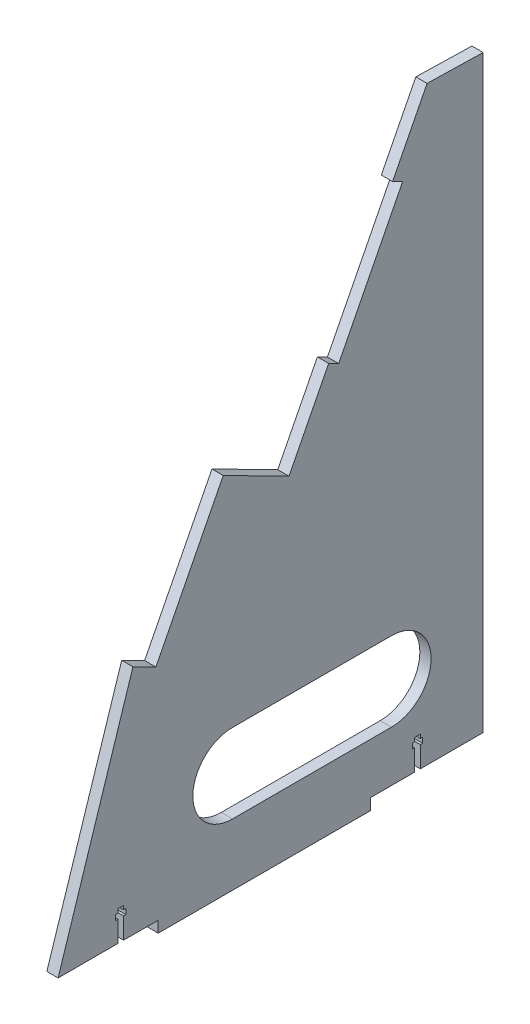
SolidWorks part; units mm, degrees
ref_plane "Front Plane" through (0, 0, 0) normal (0, 0, 1) x (1, 0, 0)
ref_plane "Top Plane" through (0, 0, 0) normal (0, 1, 0) x (1, 0, 0)
ref_plane "Right Plane" through (0, 0, 0) normal (1, 0, 0) x (0, 0, -1)
sketch "Sketch1" plane through (0, 0, 0) normal (1, 0, 0) x (0, 0, -1)
  line L8 (42.308, 123.833) -> (2.4484, 0.2585)
  line L9 (2.4484, 0.2585) -> (228.7682, 0.2585)
  line L10 (228.7682, 0.2585) -> (228.7682, 313.8431)
  line L11 (228.7682, 313.8431) -> (198.91, 314.5312)
  line L12 (125.3885, 170.1754) -> (90.3689, 188.0112)
  line L13 (90.3689, 188.0112) -> (54.5159, 117.6154)
  line L14 (54.5159, 117.6154) -> (42.308, 123.833)
  line L15 (198.91, 314.5312) -> (180.5296, 278.4423)
  line L16 (180.5296, 278.4423) -> (185.8761, 275.7192)
  line L17 (185.8761, 275.7192) -> (151.8384, 208.8879)
  line L18 (151.8384, 208.8879) -> (146.4919, 211.6109)
  line L19 (146.4919, 211.6109) -> (125.3885, 170.1754)
extrude "Boss-Extrude1" add sketch "Sketch1" along normal blind 6
sketch "Sketch2" plane through (6, 0, 0) normal (1, 0, 0) x (0, 0, -1)
  line L0 (95.2866, 48.2606) -> (179.9632, 48.2606) construction
  line L1 (95.2866, 69.3488) -> (179.9632, 69.3488)
  line L2 (95.2866, 27.1724) -> (179.9632, 27.1724)
  arc A0 (95.2866, 69.3488) -> (95.2866, 27.1724) centre (95.2866, 48.2606) ccw
  arc A1 (179.9632, 27.1724) -> (179.9632, 69.3488) centre (179.9632, 48.2606) ccw
  point P2 (137.6249, 48.2606)
extrude "Cut-Extrude1" cut sketch "Sketch2" against normal blind 6
sketch "Sketch3" plane through (0, 0.2585, 0) normal (0, -1, 0) x (1, 0, 0)
  line L0 (0, -2.4484) -> (0, -228.7682) construction
  line L1 (0, -55.7682) -> (6, -55.7682)
  line L2 (0, -55.7682) -> (0, -168.7682)
  line L3 (0, -168.7682) -> (6, -168.7682)
  line L4 (6, -55.7682) -> (6, -168.7682)
  line L5 (6, -2.4484) -> (6, -228.7682) construction
  line L6 (6, -228.7682) -> (0, -228.7682) construction
  dimension "D1" = 113
  dimension "D2" = 60
extrude "Boss-Extrude2" add sketch "Sketch3" along normal blind 6
sketch "Sketch4" plane through (6, 0, 0) normal (1, 0, 0) x (0, 0, -1)
  line L0 (2.4484, 0.2585) -> (55.7682, 0.2585) construction
  line L1 (34.2182, 0.2585) -> (37.3182, 0.2585)
  line L2 (34.2182, 0.2585) -> (34.2182, 16.2585)
  line L3 (34.2182, 16.2585) -> (37.3182, 16.2585)
  line L4 (37.3182, 0.2585) -> (37.3182, 16.2585)
  line L6 (55.7682, -5.7415) -> (55.7682, 0.2585) construction
  line L7 (168.7682, 0.2585) -> (228.7682, 0.2585) construction
  line L8 (192.2182, 0.2585) -> (195.3182, 0.2585)
  line L9 (192.2182, 0.2585) -> (192.2182, 16.2585)
  line L10 (192.2182, 16.2585) -> (195.3182, 16.2585)
  line L11 (195.3182, 0.2585) -> (195.3182, 16.2585)
  line L12 (168.7682, -5.7415) -> (168.7682, 0.2585) construction
  point P6 (35.7682, 0.2585)
  point P17 (193.7682, 0.2585)
  dimension "D1" = 3.1
  dimension "D2" = 16
  dimension "D3" = 20
  dimension "D4" = 16
  dimension "D5" = 3.1
  dimension "D6" = 25
extrude "Cut-Extrude2" cut sketch "Sketch4" against normal blind 6
sketch "Sketch5" plane through (6, 0, 0) normal (1, 0, 0) x (0, 0, -1)
  line L0 (34.2182, 16.2585) -> (34.2182, 0.2585) construction
  line L1 (33.0182, 11.4585) -> (38.5182, 11.4585)
  line L2 (33.0182, 11.4585) -> (33.0182, 14.2585)
  line L3 (33.0182, 14.2585) -> (38.5182, 14.2585)
  line L4 (38.5182, 11.4585) -> (38.5182, 14.2585)
  line L5 (37.3182, 16.2585) -> (34.2182, 16.2585) construction
  line L6 (192.2182, 16.2585) -> (192.2182, 0.2585) construction
  line L7 (191.0182, 14.2585) -> (196.5182, 14.2585)
  line L8 (191.0182, 14.2585) -> (191.0182, 11.4585)
  line L9 (191.0182, 11.4585) -> (196.5182, 11.4585)
  line L10 (196.5182, 14.2585) -> (196.5182, 11.4585)
  line L11 (195.3182, 16.2585) -> (192.2182, 16.2585) construction
  dimension "D1" = 5.5
  dimension "D2" = 2.8
  dimension "D3" = 1.2
  dimension "D4" = 2
  dimension "D5" = 5.5
  dimension "D6" = 2.8
  dimension "D7" = 1.2
  dimension "D8" = 2
extrude "Cut-Extrude3" cut sketch "Sketch5" against normal blind 6
